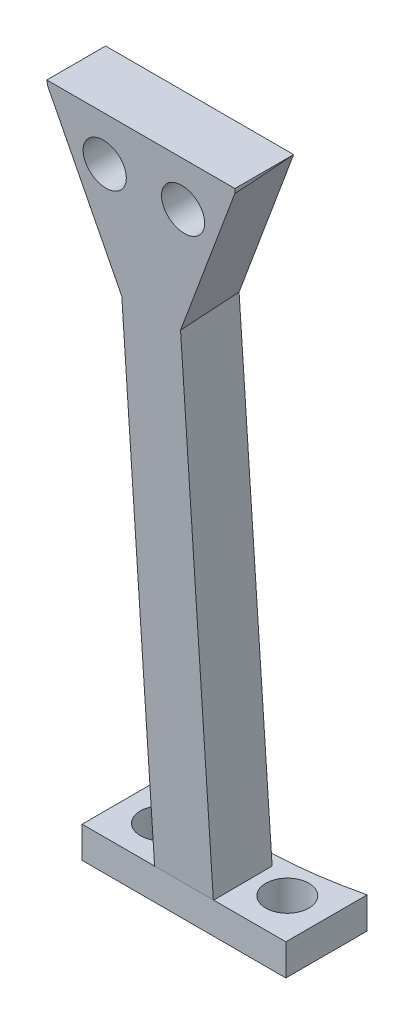
SolidWorks part; units mm, degrees
ref_plane "Front Plane" through (0, 0, 0) normal (0, 0, 1) x (1, 0, 0)
ref_plane "Top Plane" through (0, 0, 0) normal (0, 1, 0) x (1, 0, 0)
ref_plane "Right Plane" through (0, 0, 0) normal (1, 0, 0) x (0, 0, -1)
sketch "Sketch1" plane through (0, 0, 0) normal (0, 1, 0) x (1, 0, 0)
  line L0 (-6.5, 0) -> (6.5, 0)
  line L1 (-6.5, 0) -> (-6.5, 5.19)
  line L2 (6.5, 0) -> (6.5, 5.19)
  spline S0 degree 2 poles (-6.5, 5.19) (0, 3.63) (6.5, 5.19) knots 0 0 0 1 1 1
  point P4 (0, 0)
  dimension "D1" = 13
  dimension "D2" = 5.19
  dimension "D3" = 4.41
extrude "Boss-Extrude1" add sketch "Sketch1" along normal blind 2
sketch "Sketch2" plane through (0, 2, 0) normal (0, 1, 0) x (1, 0, 0)
  line L0 (-6.5, 2.595) -> (6.5, 2.595) construction
  line L1 (-6.5, 5.19) -> (-6.5, 0) construction
  line L2 (6.5, 0) -> (6.5, 5.19) construction
  circle A0 centre (-4, 2.595) radius 1.375
  circle A1 centre (4, 2.595) radius 1.375
  dimension "D3" = 2.75
  dimension "D1" = 2.5
  dimension "D2" = 2.5
extrude "Cut-Extrude1" cut sketch "Sketch2" against normal blind 2
sketch "Sketch4" plane through (0, 2, 0) normal (0, 1, 0) x (1, 0, 0)
  line L0 (-1.875, 3.75) -> (1.875, 3.75)
  line L1 (-1.875, 3.75) -> (-1.875, 0)
  line L2 (-6.5, 0) -> (6.5, 0) construction
  line L3 (-1.875, 0) -> (1.875, 0)
  line L4 (1.875, 0) -> (1.875, 3.75)
  point P2 (0, 3.75)
  dimension "D1" = 3.75
  dimension "D2" = 3.75
ref_plane "Plane1" through (0, 44.75, 0) normal (0, 1, 0) x (1, 0, 0)
sketch "Sketch6" plane through (0, 44.75, 0) normal (0, 1, 0) x (1, 0, 0)
  line L4 (-6, 1) -> (6, 1)
  line L7 (-6, 1) -> (-6, -2.75)
  line L9 (6, -2.75) -> (6, 1)
  line L10 (-1.875, 3.75) -> (-1.875, 0) construction
  line L12 (6, -2.75) -> (-6, -2.75)
  line L13 (-1.875, 0) -> (1.875, 0) construction
  point P3 (0, 1)
  dimension "D1" = 1
  dimension "D2" = 12
loft "Loft2" add profiles "Sketch4", "Sketch6"
sketch "Sketch16" plane through (0, 0.2485, -3.8627) normal (0, 0.0642, -0.9979) x (-1, 0, 0)
  line L0 (-1.875, 1.7551) -> (-1.875, 34.5935)
  line L5 (1.875, 34.5935) -> (1.875, 1.7551)
  line L6 (-6, 44.5935) -> (-1.875, 1.7551)
  line L11 (-6, 44.5935) -> (6, 44.5935) construction
  line L12 (1.875, 1.7551) -> (6, 44.5935)
  line L13 (-6, 44.5935) -> (-1.875, 34.5935)
  line L14 (6, 44.5935) -> (1.875, 34.5935)
  dimension "D2" = 10
extrude "Cut-Extrude5" cut sketch "Sketch16" against normal blind 10
sketch "Sketch12" plane through (0, 0, 0) normal (0, 0, 1) x (1, 0, 0)
  line L1 (2.8545, 44.75) -> (-2.8545, 44.75) construction
  line L2 (0, 44.75) -> (0, 0) construction
  circle A0 centre (-2.5, 41.75) radius 1.375
  circle A1 centre (2.5, 41.75) radius 1.375
  dimension "D1" = 2.75
  dimension "D2" = 3
  dimension "D3" = 3
  dimension "D4" = 2.5
  dimension "D5" = 2.5
extrude "Cut-Extrude3" cut sketch "Sketch12" against normal through all both and the other way through all
